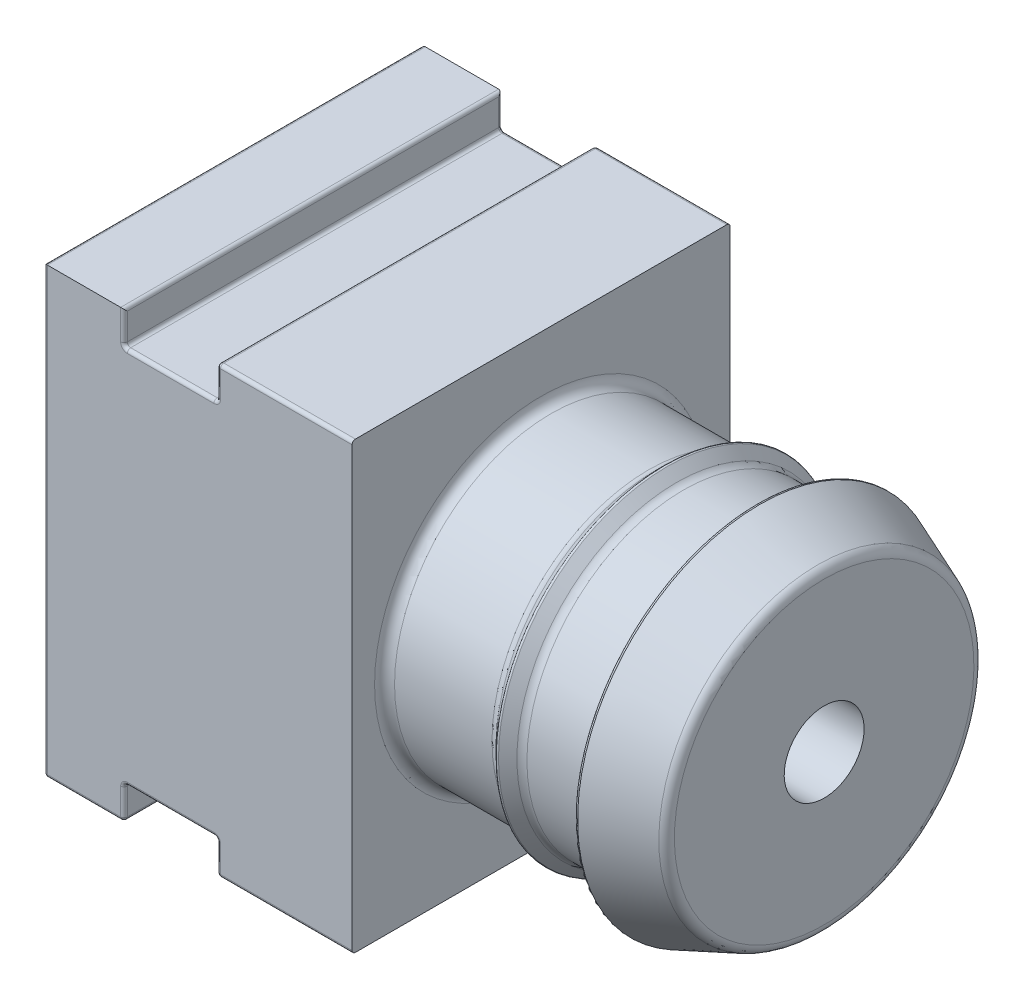
SolidWorks part; units mm, degrees
ref_plane "Front Plane" through (0, 0, 0) normal (0, 0, 1) x (1, 0, 0)
ref_plane "Top Plane" through (0, 0, 0) normal (0, 1, 0) x (1, 0, 0)
ref_plane "Right Plane" through (0, 0, 0) normal (1, 0, 0) x (0, 0, -1)
sketch "Sketch2" plane through (0, 0, 0) normal (0, 1, 0) x (1, 0, 0)
  line L0 (0, -11.35) -> (0, 11.35)
  line L1 (0, 11.35) -> (-18.5, 11.35)
  line L2 (-18.5, 11.35) -> (-18.5, -11.35)
  line L3 (-18.5, -11.35) -> (0, -11.35)
  circle A0 centre (-12.7, 0) radius 3.175
  point P4 (0, 0)
  point P10 (-18.5, 0)
  dimension "D3" = 6.35
  dimension "D4" = 5.8
  dimension "D1" = 22.7
  dimension "D2" = 12.7
extrude "Boss-Extrude2" add sketch "Sketch2" along normal mid plane 22.7
hole_wizard "#10-32 Tapped Hole1" positions "Sketch4" profile "Sketch5" tap size "#10-32" standard "ANSI Inch"
sketch "Sketch4" plane through (0, 0, -11.35) normal (0, 0, -1) x (-1, 0, 0)
  line L0 (0, 11.35) -> (0, -11.35) construction
  point P15 (4.8, 0)
  point P20 (0, 0)
  dimension "D1" = 4.8
sketch "Sketch5" plane through (-4.8, 0, -11.35) normal (1, 0, 0) x (0, 1, 0)
  line L0 (0, 0) -> (0, 14.9633)
  line L1 (0, 14.9633) -> (2.0193, 13.75)
  line L2 (2.0193, 13.75) -> (2.0193, 0)
  line L5 (2.0193, 0) -> (0, 0)
  line L10 (0, 14.9633) -> (-2.0193, 13.75) construction
  line L11 (0, -6.35) -> (0, 107.95) construction
  dimension "Tap Drill Dia." = 4.0386
  dimension "Tap Drill Depth" = 13.75
  dimension "Drill Angle" = 118
cosmetic thread "Hole Thread1" parameters "D1"=6.35, "D2"=4.826
sketch "Sketch3" plane through (0, 0, 0) normal (0, 0, 1) x (1, 0, 0)
  line L1 (0, 11.35) -> (0, -11.35) construction
  line L4 (0, 0) -> (0, 9.4)
  line L13 (17, 9.4) -> (17, 0)
  line L14 (17, 0) -> (0, 0)
  line L15 (17, 9.4) -> (13, 11)
  line L16 (13, 11) -> (13, 9.4)
  line L23 (0, 9.4) -> (6.7, 9.4)
  line L25 (8.3, 9.4) -> (7.5, 10.2)
  line L26 (7.5, 10.2) -> (6.7, 9.4)
  line L27 (8.3, 9.4) -> (13, 9.4)
  line L29 (7.5, 10.2) -> (7.5, 9.4) construction
  line L30 (8.3, 9.4) -> (7.5, 9.4) construction
  point P14 (7.5, 9.4)
  dimension "D1" = 13
  dimension "D2" = 9.4
  dimension "D3" = 4
  dimension "D4" = 1.6
  dimension "D5" = 9.5
  dimension "D6" = 0.8
revolve "Revolve1" add sketch "Sketch3" angle 360 about L14
sketch "Sketch18" plane through (17, 0, 0) normal (1, 0, 0) x (0, 0, -1)
  circle A0 centre (0, 0) radius 2.4
  dimension "D1" = 4.8
extrude "Cut-Extrude2" cut sketch "Sketch18" against normal blind 22
sketch "Sketch12" plane through (0, -11.35, 0) normal (0, -1, 0) x (1, 0, 0)
  circle A0 centre (-12.7, 0) radius 3.175
  dimension "D1" = 6.35
extrude "Boss-Extrude3" add sketch "Sketch12" against normal blind 22.7
sketch "Sketch13" plane through (0, -11.35, 0) normal (0, -1, 0) x (1, 0, 0)
  line L1 (0, 11.35) -> (-18.5, 11.35)
  line L2 (0, 11.35) -> (0, -11.35)
  line L3 (0, -11.35) -> (-18.5, -11.35)
  line L4 (-18.5, 11.35) -> (-18.5, -11.35)
extrude "Boss-Extrude4" add sketch "Sketch13" along normal blind 2
mirror "Mirror1" about plane through (0, 0, 0) normal (0, 1, 0) of "Boss-Extrude4"
sketch "Sketch15" plane through (0, 0, -11.35) normal (0, 0, -1) x (-1, 0, 0)
  line L1 (8.1, 13.35) -> (13.7, 13.35)
  line L2 (8.1, 13.35) -> (8.1, 11.35)
  line L3 (8.1, 11.35) -> (13.7, 11.35)
  line L4 (13.7, 13.35) -> (13.7, 11.35)
  line L5 (18.5, 13.35) -> (0, 13.35) construction
  line L10 (18.5, 13.35) -> (18.5, -13.35) construction
  line L11 (0, 0) -> (50000, 0) construction
  line L12 (13.7, -13.35) -> (13.7, -11.35)
  line L13 (8.1, -11.35) -> (13.7, -11.35)
  line L14 (8.1, -13.35) -> (8.1, -11.35)
  line L15 (8.1, -13.35) -> (13.7, -13.35)
  point P8 (18.5, 0)
  point P14 (8.1, 12.35)
  dimension "D1" = 2
  dimension "D3" = 4.8
  dimension "D4" = 5.6
extrude "Cut-Extrude1" cut sketch "Sketch15" against normal through all
fillet "Fillet1" radius 0.1 2 edges at (7.5, 10.2, 0) (13, 11, 0)
fillet "Fillet2" radius 0.6 5 edges at (13, 9.4, 0) (8.3, 9.4, 0) (6.7, 9.4, 0) (0, 9.4, 0) (17, 9.4, 0)
fillet "Fillet5" radius 0.2 28 edges at (-4.05, -13.35, 11.35) (-18.5, -13.35, 0) (-16.1, -13.35, -11.35) (-18.5, 13.35, 0) (-16.1, -13.35, 11.35) (-4.05, -13.35, -11.35) (-18.5, 0, 11.35) (-18.5, 0, -11.35) (-8.1, 12.35, 11.35) (-8.1, 11.35, 0) (-8.1, 13.35, 0) (-13.7, 12.35, 11.35) (-13.7, 13.35, 0) (-10.9, 11.35, 11.35) (-13.7, 11.35, 0) (-8.1, 12.35, -11.35) (-10.9, 11.35, -11.35) (-13.7, 12.35, -11.35) (-13.7, -13.35, 0) (-8.1, -12.35, 11.35) (-8.1, -13.35, 0) (-10.9, -11.35, 11.35) (-8.1, -11.35, 0) (-13.7, -12.35, 11.35) (-13.7, -11.35, 0) (-13.7, -12.35, -11.35) (-10.9, -11.35, -11.35) (-8.1, -12.35, -11.35)
